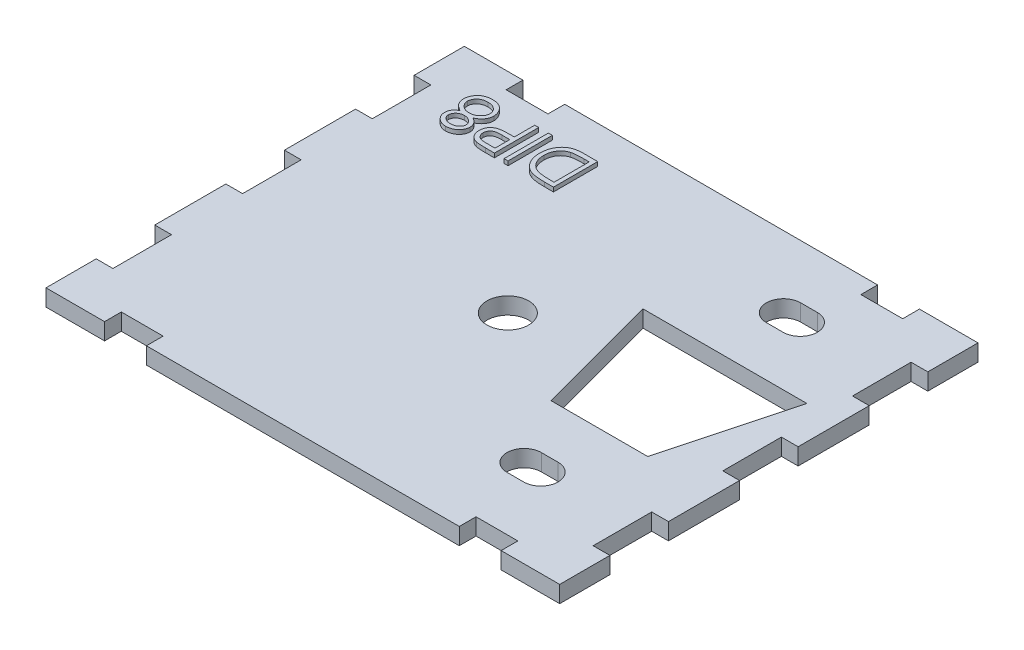
SolidWorks part; units mm, degrees
ref_plane "Front Plane" through (0, 0, 0) normal (0, 0, 1) x (1, 0, 0)
ref_plane "Top Plane" through (0, 0, 0) normal (0, 1, 0) x (1, 0, 0)
ref_plane "Right Plane" through (0, 0, 0) normal (1, 0, 0) x (0, 0, -1)
sketch "Sketch2" plane through (0, 0, 0) normal (0, 1, 0) x (1, 0, 0)
  line L1 (-50, 25) -> (50, 25)
  line L2 (-50, 25) -> (-50, -25)
  line L3 (-50, -25) -> (50, -25)
  line L4 (50, 25) -> (50, -25)
  line L5 (-50, 25) -> (50, -25) construction
  line L6 (-50, -25) -> (50, 25) construction
  point P0 (0, 0)
  dimension "D1" = 100
  dimension "D2" = 50
extrude "Boss-Extrude1" add sketch "Sketch2" along normal blind 2
sketch "Sketch12" plane through (0, 2, 0) normal (0, 1, 0) x (1, 0, 0)
  line L0 (-50, -25) -> (50, -25) construction
  line L1 (-40.2, -25) -> (-50, -25)
  line L2 (-40.2, -25) -> (-40.2, 25)
  line L3 (-40.2, 25) -> (-50, 25)
  line L4 (-50, -25) -> (-50, 25)
  line L5 (-50, -25) -> (50, -25) construction
  line L6 (41.2, -25) -> (50, -25)
  line L7 (41.2, -25) -> (41.2, 25)
  line L8 (41.2, 25) -> (50, 25)
  line L9 (50, -25) -> (50, 25)
extrude "Cut-Extrude8" cut sketch "Sketch12" against normal blind 6
sketch "Sketch13" plane through (0, 2, 0) normal (0, 1, 0) x (1, 0, 0)
  line L1 (-28.2, 19) -> (-30.2, 19)
  line L2 (-28.2, 19) -> (-28.2, 12)
  line L3 (-28.2, 12) -> (-30.2, 12)
  line L4 (-30.2, 19) -> (-30.2, 12)
  line L5 (-28.2, 3.5) -> (-30.2, 3.5)
  line L6 (-28.2, 3.5) -> (-28.2, -3.5)
  line L7 (-28.2, -3.5) -> (-30.2, -3.5)
  line L8 (-30.2, 3.5) -> (-30.2, -3.5)
  line L9 (-28.2, -12) -> (-30.2, -12)
  line L10 (-28.2, -12) -> (-28.2, -19)
  line L11 (-28.2, -19) -> (-30.2, -19)
  line L12 (-30.2, -12) -> (-30.2, -19)
  line L13 (29.2, 19) -> (31.2, 19)
  line L14 (29.2, 19) -> (29.2, 12)
  line L15 (29.2, 12) -> (31.2, 12)
  line L16 (31.2, 19) -> (31.2, 12)
  line L17 (29.2, 3.5) -> (31.2, 3.5)
  line L18 (29.2, 3.5) -> (29.2, -3.5)
  line L19 (29.2, -3.5) -> (31.2, -3.5)
  line L20 (31.2, 3.5) -> (31.2, -3.5)
  line L21 (29.2, -12) -> (31.2, -12)
  line L22 (29.2, -12) -> (29.2, -19)
  line L23 (29.2, -19) -> (31.2, -19)
  line L24 (31.2, -12) -> (31.2, -19)
  line L25 (-40.2, -25) -> (41.2, -25) construction
  line L26 (-23.2, 25) -> (-18.2, 25)
  line L27 (41.2, 25) -> (-40.2, 25) construction
  line L28 (-40.2, -25) -> (41.2, -25) construction
  line L29 (41.2, 25) -> (-40.2, 25) construction
  line L30 (-40.2, -25) -> (41.2, -25) construction
  line L31 (41.2, 25) -> (31.2, 25)
  line L32 (41.2, 25) -> (41.2, -25)
  line L33 (41.2, -25) -> (31.2, -25)
  line L34 (31.2, 25) -> (31.2, -25)
  line L35 (41.2, 25) -> (-40.2, 25) construction
  line L36 (-40.2, -25) -> (-30.2, -25)
  line L37 (-40.2, -25) -> (-40.2, 25)
  line L38 (-40.2, 25) -> (-30.2, 25)
  line L39 (-30.2, -25) -> (-30.2, 25)
  line L40 (-23.2, 25) -> (-23.2, 23)
  line L41 (-23.2, 23) -> (-18.2, 23)
  line L42 (-18.2, 25) -> (-18.2, 23)
  line L43 (-23.2, -25) -> (-18.2, -25)
  line L44 (-23.2, -25) -> (-23.2, -23)
  line L45 (-23.2, -23) -> (-18.2, -23)
  line L46 (-18.2, -25) -> (-18.2, -23)
  line L47 (24.2, -25) -> (19.2, -25)
  line L48 (24.2, -25) -> (24.2, -23)
  line L49 (24.2, -23) -> (19.2, -23)
  line L50 (19.2, -25) -> (19.2, -23)
  line L51 (24.2, 25) -> (19.2, 25)
  line L52 (24.2, 25) -> (24.2, 23)
  line L53 (24.2, 23) -> (19.2, 23)
  line L54 (19.2, 25) -> (19.2, 23)
  point P24 (29.2, 0)
  point P30 (30.2, 3.5)
  line M32 (41.2, -25) -> (41.2, 25)
  line M41 (41.2, 25) -> (-40.2, 25)
  line M42 (-40.2, 25) -> (-40.2, -25)
  line M47 (-40.2, -25) -> (41.2, -25)
  dimension "D1" = 2
  dimension "D2" = 2
  dimension "D3" = 2
  dimension "D4" = 2
  dimension "D5" = 2
  dimension "D6" = 2
  dimension "D7" = 57.4
  dimension "D8" = 57.4
  dimension "D9" = 57.4
  dimension "D10" = 7
  dimension "D11" = 7
  dimension "D12" = 7
  dimension "D13" = 7
  dimension "D14" = 7
  dimension "D15" = 7
  dimension "D16" = 5
  dimension "D17" = 2
  dimension "D18" = 5
  dimension "D19" = 6
  dimension "D20" = 8.5
  dimension "D21" = 8.5
  dimension "D22" = 6
  dimension "D23" = 6
  dimension "D24" = 8.5
  dimension "D25" = 8.5
  dimension "D26" = 6
  dimension "D27" = 5
  dimension "D28" = 5
  dimension "D29" = 2
  dimension "D30" = 2
  dimension "D31" = 5
  dimension "D32" = 5
  dimension "D33" = 5
  dimension "D34" = 5
  dimension "D35" = 2
extrude "Cut-Extrude10" cut sketch "Sketch13" against normal blind 6 contours L5 L8 L7 L6 | L39 L12 L8 L4 M47 M41 M42 | L1 L4 L3 L2 | L50 L48 L49 M47 | L24 L21 L22 L23 | L20 L17 L18 L19 | L16 L13 L14 L15 | L54 L53 L52 M41 | L9 L12 L11 L10 | L34 L16 L20 L24 M41 M47 M32 | L26 L42 L41 L40 | L45 L46 L43 L44
sketch "Sketch15" plane through (0, 0, 0) normal (0, -1, 0) x (1, 0, 0)
  line L0 (24.2, 23) -> (19.2, 23) construction
  line L16 (20.7242, -7.5) -> (20.7242, -8.5)
  line L17 (20.7242, -7.5) -> (25.936, -7.5)
  line L18 (25.936, -7.5) -> (22.4527, 5.5)
  line L19 (22.4527, 5.5) -> (12.4527, 5.5)
  line L20 (12.4527, 5.5) -> (8.9693, -7.5)
  line L21 (8.9693, -7.5) -> (14.1811, -7.5)
  line L22 (14.1811, -7.5) -> (14.1811, -8.5)
  line L23 (14.1811, -8.5) -> (7.6661, -8.5)
  line L24 (7.6661, -8.5) -> (11.6853, 6.5)
  line L25 (11.6853, 6.5) -> (23.22, 6.5)
  line L26 (23.22, 6.5) -> (27.2392, -8.5)
  line L27 (27.2392, -8.5) -> (20.7242, -8.5)
  line L28 (20.7242, -8.5) -> (14.1811, -8.5)
  line L29 (14.1811, -7.5) -> (20.7242, -7.5)
  line L31 (29.2, 12) -> (29.2, 19) construction
  dimension "D4" = 16.5
  dimension "D18" = 11.5347
  dimension "D19" = 15.5291
  dimension "D20" = 15.5291
  dimension "D21" = 13.4586
  dimension "D22" = 13.4586
  dimension "D23" = 10
  dimension "D24" = 5.2118
  dimension "D25" = 5.2118
  dimension "D26" = 6.515
  dimension "D27" = 6.515
  dimension "D28" = 1
  dimension "D29" = 105
  dimension "D30" = 105
  dimension "D31" = 75
  dimension "D32" = 75
  dimension "D33" = 5.98
  dimension "D34" = 1
extrude "Cut-Extrude13" cut sketch "Sketch15" against normal blind 10 contours L21 L29 L17 L18 L19 L20 | L27 L26 L25 L24 L23 L22 L21 L20 L19 L18 L17 L16 | L29 L22 L28 L16
sketch "Sketch16" plane through (0, 0, 0) normal (0, -1, 0) x (-1, 0, 0)
  circle A0 centre (0, 0) radius 2.5
  dimension "D1" = 5
extrude "Cut-Extrude14" cut sketch "Sketch16" against normal blind 10 contours A0
sketch "Sketch17" plane through (0, 0, 0) normal (0, -1, 0) x (-1, 0, 0)
  line L0 (-16.4527, 18.55) -> (-18.4527, 18.55)
  line L1 (-16.4527, 14.45) -> (-18.4527, 14.45)
  line L2 (-27.2392, 8.5) -> (-7.6661, 8.5) construction
  line L3 (-16.4527, -12.45) -> (-18.4527, -12.45)
  line L4 (-11.6853, -6.5) -> (-23.22, -6.5) construction
  line L5 (-18.4527, -16.55) -> (-16.4527, -16.55)
  circle A0 centre (-17.4527, -14.5) radius 2.05
  circle A1 centre (-17.4527, 16.5) radius 2.05
  circle A2 centre (-16.4527, 16.5) radius 2.05
  circle A3 centre (-18.4527, 16.5) radius 2.05
  circle A4 centre (-18.4527, -14.5) radius 2.05
  circle A5 centre (-16.4527, -14.5) radius 2.05
  dimension "D1" = 4.1
  dimension "D2" = 4.1
  dimension "D9" = 1
  dimension "D10" = 0
  dimension "D12" = 0
  dimension "D15" = 0
  dimension "D16" = 0
  dimension "D3" = 8
  dimension "D4" = 9.7866
  dimension "D5" = 9.7866
  dimension "D6" = 5.7673
  dimension "D7" = 5.7673
  dimension "D8" = 8
  dimension "D11" = 1
  dimension "D13" = 1
  dimension "D14" = 1
extrude "Cut-Extrude15" cut sketch "Sketch17" against normal blind 3.5 contours A4 A0 | A5 A4 A0 | A4 A5 | A0 A5 A4 | A5 A0 | A5 L3 A0 | A5 A0 A4 | A4 A0 L3 | A5 A0 L5 | A5 A4 A0 | A4 L5 A0 | A2 A3 | A1 A3 A2 | A3 A1 | A3 A2 A1 | A3 A1 A2 | A3 A2 A1 | A2 A1 | A2 A1 L1 | A3 L1 A1 | A3 A1 L0 | A2 L0 A1
sketch "Sketch22" plane through (0, 2, 0) normal (0, 1, 0) x (1, 0, 0)
  line L0 (-24.5837, 20.5398) -> (4.8961, 20.5398) construction
  text T0 "DIP8" font "Century Gothic" height in points 20
extrude "Boss-Extrude4" add sketch "Sketch22" along normal blind 0.5
